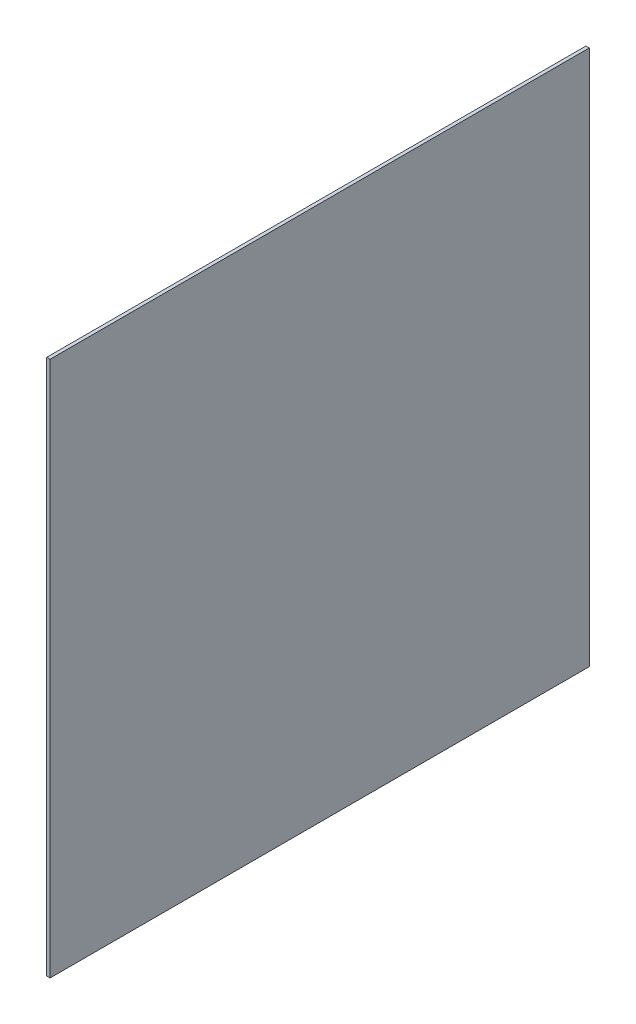
SolidWorks part; units mm, degrees
material "Acrylic (Medium-high impact)"
ref_plane "Front Plane" through (0, 0, 0) normal (0, 0, 1) x (1, 0, 0)
ref_plane "Top Plane" through (0, 0, 0) normal (0, 1, 0) x (1, 0, 0)
ref_plane "Right Plane" through (0, 0, 0) normal (1, 0, 0) x (0, 0, -1)
sketch "Sketch1" plane through (0, 0, 0) normal (1, 0, 0) x (0, 0, -1)
  line L1 (-255.5875, -254) -> (255.5875, -254)
  line L2 (-255.5875, -254) -> (-255.5875, 254)
  line L3 (-255.5875, 254) -> (255.5875, 254)
  line L4 (255.5875, -254) -> (255.5875, 254)
  line L5 (-255.5875, -254) -> (255.5875, 254) construction
  line L6 (-255.5875, 254) -> (255.5875, -254) construction
  point P0 (0, 0)
  dimension "D1" = 508
  dimension "D2" = 511.175
extrude "Boss-Extrude1" add sketch "Sketch1" along normal mid plane 3.175
equation "\"D1@Sketch1\"=\"BOX SIZE\""
equation "\"BOX SIZE\"= 20"
equation "\"STANDARD PROFILE\"= 1"
equation "\"BOX PLATE THK\"= .125"
equation "\"D2@Sketch1\"=\"BOX DEPTH\""
equation "\"D1@Boss-Extrude1\"= \"BOX PLATE THK\""
equation "\"BIG FACE DEPTH\"= 1.25"
equation "\"BOX DEPTH\"= \"BOX SIZE\"+\"BOX PLATE THK\""
